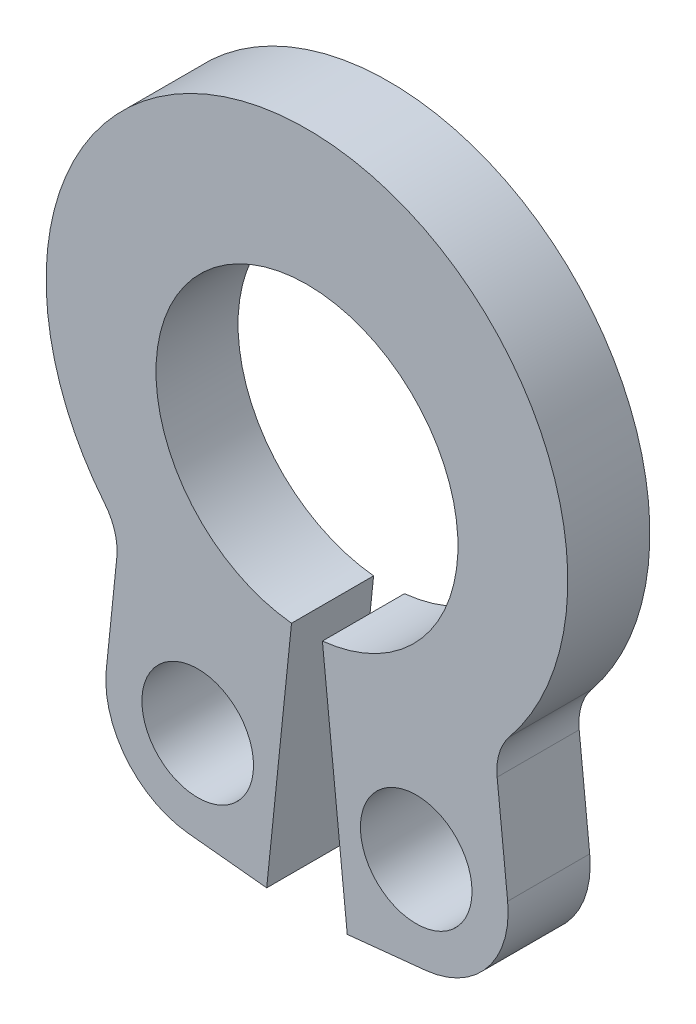
SolidWorks part; units mm, degrees
extrude "Body" add sketch "BodySke" against normal blind 0.635
sketch "BodySke" plane through (0, 0, 0) normal (0, 0, 1) x (1, 0, 0)
  line L0 (-1.5431, 0) -> (1.5431, 0) construction
  line L1 (0, 0) -> (0, 2.2098) construction
  line L2 (0.1195, -1.1623) -> (0.3117, -3.032)
  line L3 (-0.1195, -1.1623) -> (-0.3117, -3.032)
  line L4 (0, 0) -> (1.3282, -1.3282) construction
  line L5 (0, 0) -> (-1.3282, -1.3282) construction
  line L6 (0.3117, -3.032) -> (0.9181, -2.9697)
  line L7 (-0.3117, -3.032) -> (-0.9181, -2.9697)
  line L9 (1.4715, -1.3983) -> (1.5528, -2.1895)
  line L14 (-1.4715, -1.3983) -> (-1.5528, -2.1895)
  circle A0 centre (0, 0) radius 1.1684 construction
  arc A1 (0.1195, -1.1623) -> (-0.1195, -1.1623) centre (0, 0) ccw
  arc A2 (1.3282, -1.3282) -> (-1.3282, -1.3282) centre (0, 0.1915) ccw construction
  arc A3 (-1.5528, -2.1895) -> (-0.9181, -2.9697) centre (-0.8454, -2.2622) ccw
  arc A4 (-1.4715, -1.3983) -> (-1.566, -1.0817) centre (-1.901, -1.3541) ccw
  arc A5 (1.566, -1.0817) -> (1.4715, -1.3983) centre (1.901, -1.3541) ccw
  arc A6 (0.9181, -2.9697) -> (1.5528, -2.1895) centre (0.8454, -2.2622) ccw
  arc A7 (1.566, -1.0817) -> (-1.566, -1.0817) centre (0, 0.1915) ccw
  dimension "GrooveDia" = 2.3368
  dimension "LugFilletRad" = 0.7112
  dimension "BodyFilletRad" = 0.4318
  dimension "LargeRad" = 2.2098
  dimension "SmallRad" = 1.8783
  dimension "LugY" = 3.048
  dimension "GapAng" = 11.739
  dimension "LugWidth" = 1.3208
  dimension "D2" = 90
ref_plane "Plane1" through (0, 0, 0) normal (0, 0, 1) x (1, 0, 0)
ref_plane "Plane2" through (0, 0, 0) normal (0, 1, 0) x (1, 0, 0)
ref_plane "Plane3" through (0, 0, 0) normal (1, 0, 0) x (0, 0, -1)
sketch "Clipboard" plane through (0, 0, 0) normal (0, 0, 1) x (1, 0, 0)
  line L0 (0, 0) -> (1.7272, 0)
  line L1 (0, 0) -> (0, 5.2578)
  line L2 (0, 0) -> (0, -1.8796)
  line L3 (0, 0) -> (-1.016, 0)
  circle A0 centre (0, 0) radius 0.4318
  circle A1 centre (0, 0) radius 1.1684
  circle A2 centre (0, 0) radius 1.1303
  dimension "HoleDia" = 0.8636
  dimension "ShaftDia" = 2.3368
  dimension "FreeDia" = 2.2606
  dimension "LargeSection" = 1.7272
  dimension "RingHeight" = 5.2578
  dimension "LugSection" = 1.8796
  dimension "LugBasis" = 1.016
sketch "HolSke" plane through (0, 0, 0) normal (0, 0, 1) x (1, 0, 0)
  line L0 (0, 0) -> (0, -2.9285) construction
  line L1 (0.3117, -3.032) -> (0.9181, -2.9697) construction
  line L2 (0.1195, -1.1623) -> (0.3117, -3.032) construction
  circle A0 centre (0.8454, -2.2622) radius 0.4318
  circle A1 centre (-0.8454, -2.2622) radius 0.4318
  dimension "HoleDia" = 0.8636
extrude "Holes" cut sketch "HolSke" against normal through all
sketch "NotSke" plane through (0, 0, 0) normal (0, 0, 1) x (1, 0, 0)
  line L2 (0, 0) -> (0, -3.0231) construction
  arc A0 (0.5202, -2.4862) -> (0.3434, -1.6409) centre (0.4318, -2.0635) ccw
  arc A1 (-0.3434, -1.6409) -> (-0.5202, -2.4862) centre (-0.4318, -2.0635) ccw
  arc A2 (-0.8432, -1.9322) -> (0.8432, -1.9322) centre (0, 0) ccw construction
  arc A3 (0.1195, -1.1623) -> (-0.1195, -1.1623) centre (0, 0) ccw construction
  circle A4 centre (0.4318, -2.0635) radius 0.4318 construction
  circle A5 centre (-0.4318, -2.0635) radius 0.4318 construction
  arc A6 (-0.3434, -1.6409) -> (0.3434, -1.6409) centre (0, 0) ccw
  arc A7 (-0.5202, -2.4862) -> (0.5202, -2.4862) centre (0, 0) ccw
  dimension "HoleDia" = 0.8636
extrude "Notch" [suppressed] cut sketch "NotSke" against normal through all
fillet "NotchFillets" [suppressed] radius 0.2478
equation "' \"ShaftDia@Clipboard\" = 0.058"
equation "' \"FreeDia@Clipboard\" = 0.055"
equation "' \"Thickness@Body\" = 0.015"
equation "' \"GrooveDia@BodySke\" = 0.058"
equation "' \"LugSection@Clipboard\" = 0.066"
equation "' \"RingHeight@Clipboard\" = 0.145"
equation "' \"HoleDia@Clipboard\" = 0.035"
equation "' \"LugBasis@Clipboard\" = 0.03"
equation "' \"ShaftDia@Clipboard\" = 0.092"
equation "' \"FreeDia@Clipboard\" = 0.089"
equation "' \"Thickness@Body\" = 0.025"
equation "' \"GrooveDia@BodySke\" = 0.092"
equation "' \"LugSection@Clipboard\" = 0.074"
equation "' \"RingHeight@Clipboard\" = 0.207"
equation "' \"HoleDia@Clipboard\" = 0.034"
equation "' \"LugBasis@Clipboard\" = 0.04"
equation "\"LargeRad@BodySke\" =  \"RingHeight@Clipboard\" - \"GrooveDia@BodySke\" / 2  - \"LugSection@Clipboard\""
equation "\"SmallRad@BodySke\" = \"LargeRad@BodySke\" * 0.85"
equation "\"LugY@BodySke\" =  \"GrooveDia@BodySke\" / 2 +  \"LugSection@Clipboard\" "
equation "\"GapAng@BodySke\" = 360 - 360 * (\"FreeDia@Clipboard\" /  \"GrooveDia@BodySke\" )"
equation "\"HoleDia@NotSke\" = \"HoleDia@Clipboard\""
equation "\"NotchRad@NotSke\" = \"LugY@BodySke\" - \"LugSection@Clipboard\" / 2"
equation "\"Radius@NotchFillets\" = (\"LugSection@Clipboard\" - \"HoleDia@Clipboard\" ) / 4.1"
equation "\"LugWidth@BodySke\" = \"LugBasis@Clipboard\"  * 1.3"
equation "\"LugFilletRad@BodySke\" = \"LugBasis@Clipboard\"  * 0.7"
equation "\"BodyFilletRad@BodySke\" = \"HoleDia@Clipboard\" / 2"
equation "\"HoleOffset@HolSke\" =  \"LugBasis@Clipboard\"  * 0.6"
equation "\"HoleInset@HolSke\" = \"LugBasis@Clipboard\"  * 0.7"
equation "\"HoleDia@HolSke\" = \"HoleDia@Clipboard\""
